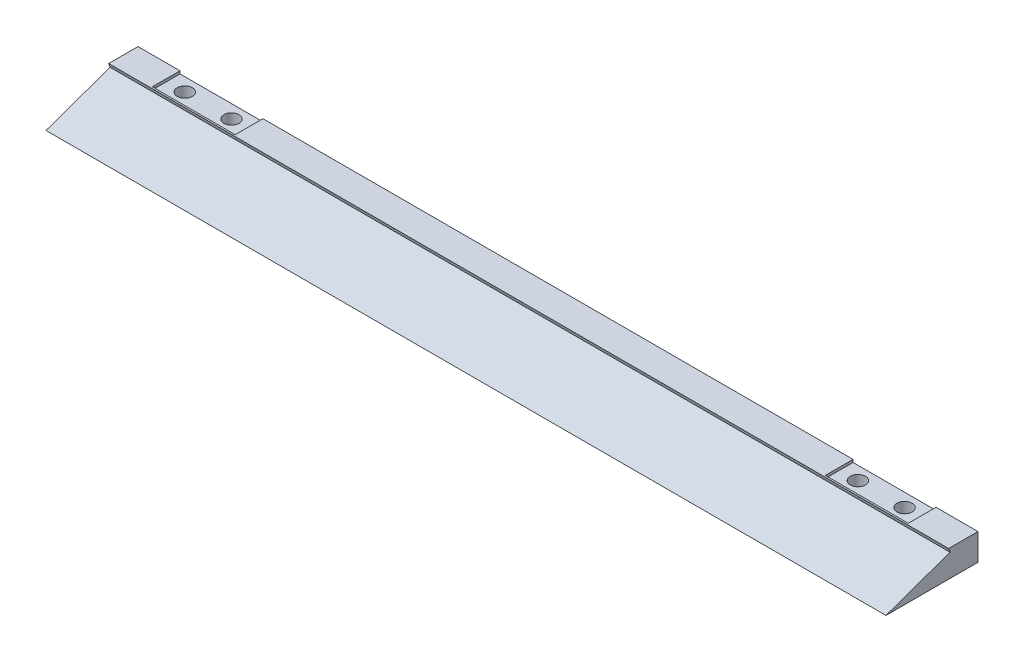
SolidWorks part; units mm, degrees
material "1023 Carbon Steel Sheet (SS)"
ref_plane "Front Plane" through (0, 0, 0) normal (0, 0, 1) x (1, 0, 0)
ref_plane "Top Plane" through (0, 0, 0) normal (0, 1, 0) x (1, 0, 0)
ref_plane "Right Plane" through (0, 0, 0) normal (1, 0, 0) x (0, 0, -1)
sketch "Sketch1" plane through (0, 0, 0) normal (0, 1, 0) x (1, 0, 0)
  line L1 (-100, -15) -> (100, -15)
  line L2 (-100, -15) -> (-100, 15)
  line L3 (-100, 15) -> (100, 15)
  line L4 (100, -15) -> (100, 15)
  line L5 (-100, -15) -> (100, 15) construction
  line L6 (-100, 15) -> (100, -15) construction
  point P0 (0, 0)
  dimension "D1" = 200
  dimension "D2" = 30
extrude "Base" add sketch "Sketch1" along normal blind 6.35
ref_plane "Midplane" through (0, 0, 0) normal (1, 0, 0) x (0, 0, -1)
sketch "Sketch2" plane through (100, 0, 0) normal (1, 0, 0) x (0, 0, -1)
  line L0 (-6.9075, 0) -> (11, 6.35)
  line L1 (-15, 0) -> (15, 0) construction
  line L2 (-15, 6.35) -> (15, 6.35) construction
  line L3 (11, 6.35) -> (11, 0)
  line L4 (11, 0) -> (-6.9075, 0)
  line L5 (15, 6.35) -> (15, 0) construction
  line L7 (11, 6.35) -> (-15, 6.35)
  line L8 (-15, 6.35) -> (-15, 0)
  line L9 (-15, 0) -> (-6.9075, 0)
  line L10 (8.3421, 5.4075) -> (8.0079, 6.35)
  line M3 (-15, 0) -> (15, 0)
  line M5 (15, 6.35) -> (-15, 6.35)
  line M6 (-15, 6.35) -> (-15, 0)
  dimension "D1" = 19
  dimension "D2" = 4
  dimension "D3" = 1
extrude "WedgeCut" cut sketch "Sketch2" against normal up to next contours L0 M3 M5 M6
sketch "Sketch3" plane through (0, 6.35, 0) normal (0, 1, 0) x (1, 0, 0)
  line L0 (-100, 15) -> (-100, 8.0079) construction
  line L1 (-90, 8.396) -> (-70.254, 8.396)
  line L2 (-90, 8.396) -> (-90, 15)
  line L3 (-90, 15) -> (-70.254, 15)
  line L4 (-70.254, 8.396) -> (-70.254, 15)
  line L5 (-90, 8.396) -> (-70.254, 15) construction
  line L6 (-90, 15) -> (-70.254, 8.396) construction
  line L7 (70.254, 15) -> (90, 15)
  line L8 (70.254, 15) -> (70.254, 8.396)
  line L9 (70.254, 8.396) -> (90, 8.396)
  line L10 (90, 15) -> (90, 8.396)
  line L11 (70.254, 15) -> (90, 8.396) construction
  line L12 (70.254, 8.396) -> (90, 15) construction
  line L13 (100, 15) -> (-100, 15) construction
  line L14 (100, 8.0079) -> (100, 15) construction
  point P0 (-80.127, 11.698)
  point P5 (80.127, 11.698)
  dimension "D1" = 6.604
  dimension "D2" = 19.746
  dimension "D3" = 10
  dimension "D4" = 19.746
  dimension "D5" = 10
  dimension "D6" = 6.604
extrude "Hinge Cutout" cut sketch "Sketch3" against normal blind 0.635
sketch "Sketch4" plane through (0, 5.715, 0) normal (0, 1, 0) x (1, 0, 0)
  line L0 (90, 15) -> (70.254, 15) construction
  circle A0 centre (74.5644, 11.825) radius 1.8034
  circle A1 centre (85.6896, 11.825) radius 1.8034
  point P6 (80.127, 15)
  dimension "D5" = 3.6068
  dimension "D6" = 3.6068
  dimension "D1" = 5.5626
  dimension "D2" = 5.5626
  dimension "D3" = 3.175
  dimension "D4" = 3.175
extrude "Hinge Hole Cut" cut sketch "Sketch4" against normal up to next
sketch "Sketch5" plane through (0, 0, 0) normal (0, -1, 0) x (1, 0, 0)
  line L1 (72.0394, -14.35) -> (77.0894, -14.35)
  line L2 (72.0394, -14.35) -> (72.0394, -9.3)
  line L3 (72.0394, -9.3) -> (77.0894, -9.3)
  line L4 (77.0894, -14.35) -> (77.0894, -9.3)
  line L5 (72.0394, -14.35) -> (77.0894, -9.3) construction
  line L6 (72.0394, -9.3) -> (77.0894, -14.35) construction
  line L7 (83.1646, -14.35) -> (88.2146, -14.35)
  line L8 (83.1646, -14.35) -> (83.1646, -9.3)
  line L9 (83.1646, -9.3) -> (88.2146, -9.3)
  line L10 (88.2146, -14.35) -> (88.2146, -9.3)
  line L11 (83.1646, -14.35) -> (88.2146, -9.3) construction
  line L12 (83.1646, -9.3) -> (88.2146, -14.35) construction
  point P0 (74.5644, -11.825)
  point P6 (85.6896, -11.825)
  dimension "D1" = 5.05
  dimension "D2" = 5.05
  dimension "D3" = 5.05
  dimension "D4" = 5.05
extrude "Hinge Nut Cut" cut sketch "Sketch5" against normal blind 2
mirror "Hinge Hole Mirror" about plane through (0, 0, 0) normal (1, 0, 0) of "Hinge Nut Cut", "Hinge Hole Cut"
